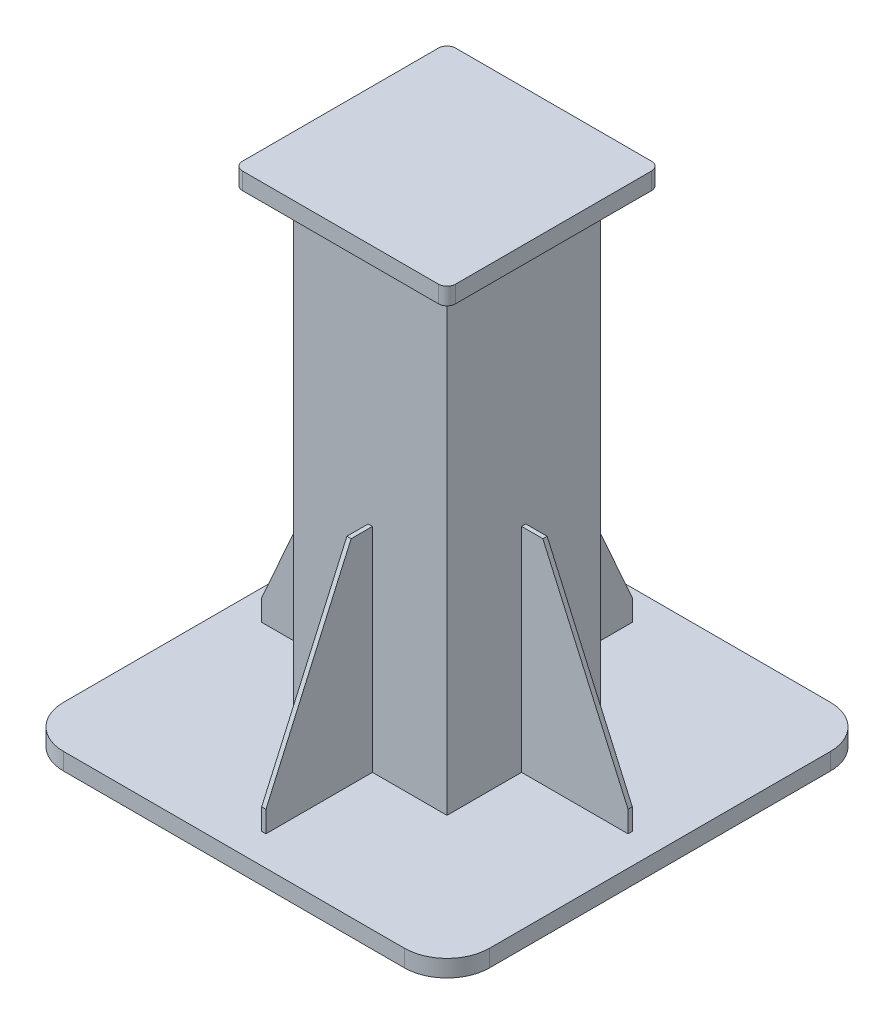
SolidWorks part; units mm, degrees
ref_plane "Front Plane" through (0, 0, 0) normal (0, 0, 1) x (1, 0, 0)
ref_plane "Top Plane" through (0, 0, 0) normal (0, 1, 0) x (1, 0, 0)
ref_plane "Right Plane" through (0, 0, 0) normal (1, 0, 0) x (0, 0, -1)
sketch "Sketch1" plane through (0, 0, 0) normal (0, 1, 0) x (1, 0, 0)
  line L1 (250, -250) -> (-250, -250)
  line L2 (250, -250) -> (250, 250)
  line L3 (250, 250) -> (-250, 250)
  line L4 (-250, -250) -> (-250, 250)
  line L5 (250, -250) -> (-250, 250) construction
  line L6 (250, 250) -> (-250, -250) construction
  point P0 (0, 0)
  dimension "D1" = 500
extrude "Boss-Extrude1" add sketch "Sketch1" along normal blind 20
sketch "Sketch2" plane through (0, 20, 0) normal (0, 1, 0) x (1, 0, 0)
  line L1 (90, -90) -> (-90, -90)
  line L2 (90, -90) -> (90, 90)
  line L3 (90, 90) -> (-90, 90)
  line L4 (-90, -90) -> (-90, 90)
  line L5 (90, -90) -> (-90, 90) construction
  line L6 (90, 90) -> (-90, -90) construction
  point P0 (0, 0)
  dimension "D1" = 180
extrude "Boss-Extrude2" add sketch "Sketch2" along normal blind 550
sketch "Sketch3" plane through (0, 570, 0) normal (0, 1, 0) x (1, 0, 0)
  line L1 (125, -125) -> (-125, -125)
  line L2 (125, -125) -> (125, 125)
  line L3 (125, 125) -> (-125, 125)
  line L4 (-125, -125) -> (-125, 125)
  line L5 (125, -125) -> (-125, 125) construction
  line L6 (125, 125) -> (-125, -125) construction
  point P0 (0, 0)
  dimension "D1" = 250
extrude "Boss-Extrude3" add sketch "Sketch3" along normal blind 20
other "Gusset1" parameters "D1"=5, "D2"=5, "D3"=0, "D4"=0, "D10"=5, "D11"=250, "D12"=125, "D13"=25, "D14"=66.038, "D15"=25
sketch "Sketch4" plane through (0, 20, 90) normal (1, 0, 0) x (0, 0, -1)
  line L0 (0, 0) -> (0, 250)
  line L1 (0, 0) -> (-125, 0)
  line L2 (-25, 250) -> (-125, 25)
  line L3 (0, 250) -> (-25, 250)
  line L4 (-125, 0) -> (-125, 25)
other "Gusset2" parameters "D1"=5, "D2"=5, "D3"=0, "D4"=0, "D10"=5, "D11"=250, "D12"=125, "D13"=25, "D14"=66.038, "D15"=25
sketch "Sketch5" plane through (-90, 20, 0) normal (0, 0, 1) x (1, 0, 0)
  line L0 (0, 0) -> (0, 250)
  line L1 (0, 0) -> (-125, 0)
  line L2 (-25, 250) -> (-125, 25)
  line L3 (0, 250) -> (-25, 250)
  line L4 (-125, 0) -> (-125, 25)
other "Gusset3" parameters "D1"=5, "D2"=5, "D3"=0, "D4"=0, "D10"=5, "D11"=250, "D12"=125, "D13"=25, "D14"=66.038, "D15"=25
sketch "Sketch6" plane through (90, 20, 0) normal (0, 0, -1) x (-1, 0, 0)
  line L0 (0, 0) -> (0, 250)
  line L1 (0, 0) -> (-125, 0)
  line L2 (-25, 250) -> (-125, 25)
  line L3 (0, 250) -> (-25, 250)
  line L4 (-125, 0) -> (-125, 25)
other "Gusset4" parameters "D1"=5, "D2"=5, "D3"=0, "D4"=0, "D10"=5, "D11"=250, "D12"=125, "D13"=25, "D14"=66.038, "D15"=25
sketch "Sketch7" plane through (0, 20, -90) normal (-1, 0, 0) x (0, 0, 1)
  line L0 (0, 0) -> (0, 250)
  line L1 (0, 0) -> (-125, 0)
  line L2 (-25, 250) -> (-125, 25)
  line L3 (0, 250) -> (-25, 250)
  line L4 (-125, 0) -> (-125, 25)
fillet "Fillet1" radius 10 4 edges at (125, 580, -125) (-125, 580, -125) (-125, 580, 125) (125, 580, 125)
fillet "Fillet2" radius 50 4 edges at (-250, 10, -250) (250, 10, -250) (-250, 10, 250) (250, 10, 250)
